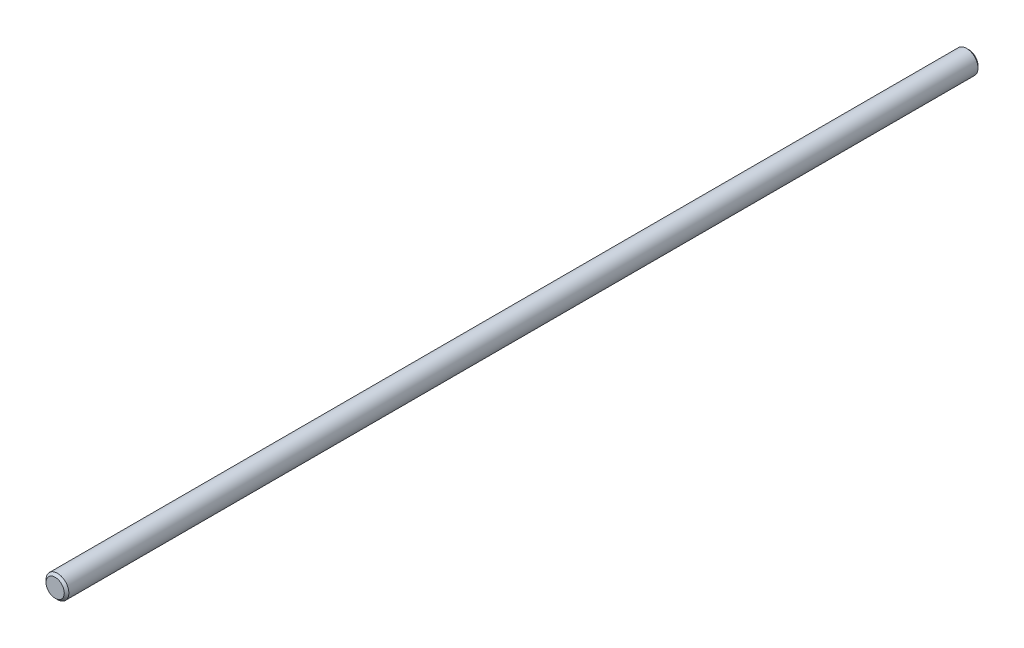
SolidWorks part; units mm, degrees
ref_plane "Front" through (0, 0, 0) normal (0, 0, 1) x (1, 0, 0)
ref_plane "Top" through (0, 0, 0) normal (0, 1, 0) x (1, 0, 0)
ref_plane "Right" through (0, 0, 0) normal (1, 0, 0) x (0, 0, -1)
sketch "Sketch1" plane through (0, 0, 0) normal (0, 0, 1) x (1, 0, 0)
  circle A0 centre (0, 0) radius 4.7625
  dimension "Diameter" = 9.525
sketch "Sketch2" plane through (0, 0, 0) normal (1, 0, 0) x (0, 0, -1)
  line L0 (-190.5, 0) -> (190.5, 0) construction
  line L1 (-139.7, 4.7625) -> (-139.7, -4.7625) construction
  line L2 (5.2387, 0) -> (-5.2387, 0) construction
  line L3 (139.7, 4.7625) -> (139.7, -4.7625) construction
  line L4 (-190.5, 4.7625) -> (-190.5, -4.7625) construction
  line L5 (190.5, 4.7625) -> (190.5, -4.7625) construction
  point P3 (-139.7, 0)
  point P8 (0, 0)
  point P9 (139.7, 0)
  point P15 (-190.5, 0)
  point P18 (190.5, 0)
  dimension "D1" = 9.525
  dimension "Length" = 381
  dimension "D2" = 50.8
  dimension "D3" = 50.8
sketch "Sketch3" plane through (0, 0, 0) normal (0, 0, 1) x (1, 0, 0)
  circle A0 centre (0, 0) radius 4.7625
  dimension "D1" = 9.525
extrude "Boss-Extrude1" add sketch "Sketch3" along normal mid plane 381
chamfer "Chamfer1" distance 0.9525 angle 45 2 edges at (4.7625, 0, -190.5) (4.7625, 0, 190.5)
equation "\"D1@Sketch3\" = \"Diameter@Sketch1\""
equation "\"D1@Boss-Extrude1\" = \"Length@Sketch2\""
equation "\"D1@Chamfer1\" = \"Diameter@Sketch1\" * .1"
equation "\"D1@Sketch2\" = \"Diameter@Sketch1\""
